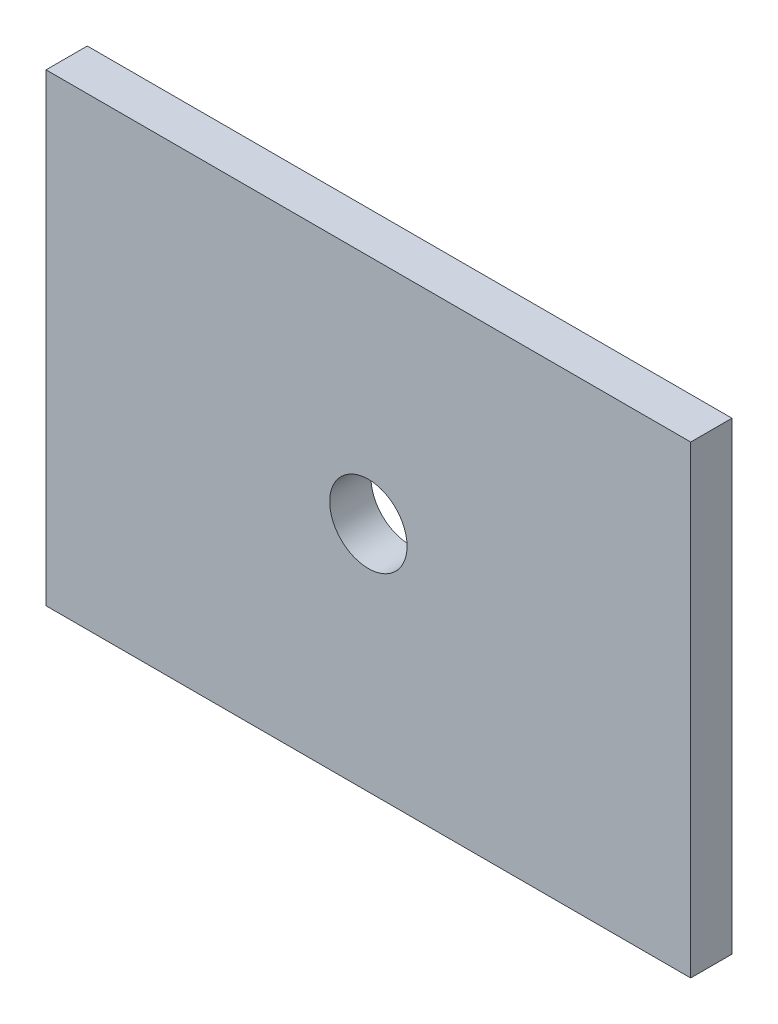
SolidWorks part; units mm, degrees
material "Q235A"
ref_plane "前视" through (0, 0, 0) normal (0, 0, 1) x (1, 0, 0)
ref_plane "上视" through (0, 0, 0) normal (0, 1, 0) x (1, 0, 0)
ref_plane "右视" through (0, 0, 0) normal (1, 0, 0) x (0, 0, -1)
sketch "草图1" plane through (0, 0, 0) normal (0, 0, 1) x (1, 0, 0)
  line L1 (125, -90) -> (-125, -90)
  line L2 (125, -90) -> (125, 90)
  line L3 (125, 90) -> (-125, 90)
  line L4 (-125, -90) -> (-125, 90)
  line L5 (125, -90) -> (-125, 90) construction
  line L6 (125, 90) -> (-125, -90) construction
  point P0 (0, 0)
  dimension "D1" = 180
  dimension "D2" = 250
extrude "凸台-拉伸1" add sketch "草图1" along normal blind 16
hole_wizard "Ø6.0 (6) 直径孔1" positions "草图3" profile "草图2" hole size "Ø6.0" standard "GB"
sketch "草图3" plane through (0, 0, 16) normal (0, 0, 1) x (1, 0, 0)
  point P0 (0, 0)
sketch "草图2" plane through (0, 0, 16) normal (1, 0, 0) x (0, -1, 0)
  line L0 (0, 0) -> (0, 29.0129)
  line L1 (0, 29.0129) -> (15, 20)
  line L2 (15, 20) -> (15, 0)
  line L5 (15, 0) -> (0, 0)
  line L10 (0, 29.0129) -> (-15, 20) construction
  line L11 (0, -6.35) -> (0, 107.95) construction
  dimension "孔直径" = 30
  dimension "孔深度" = 20
  dimension "导头角度" = 118
